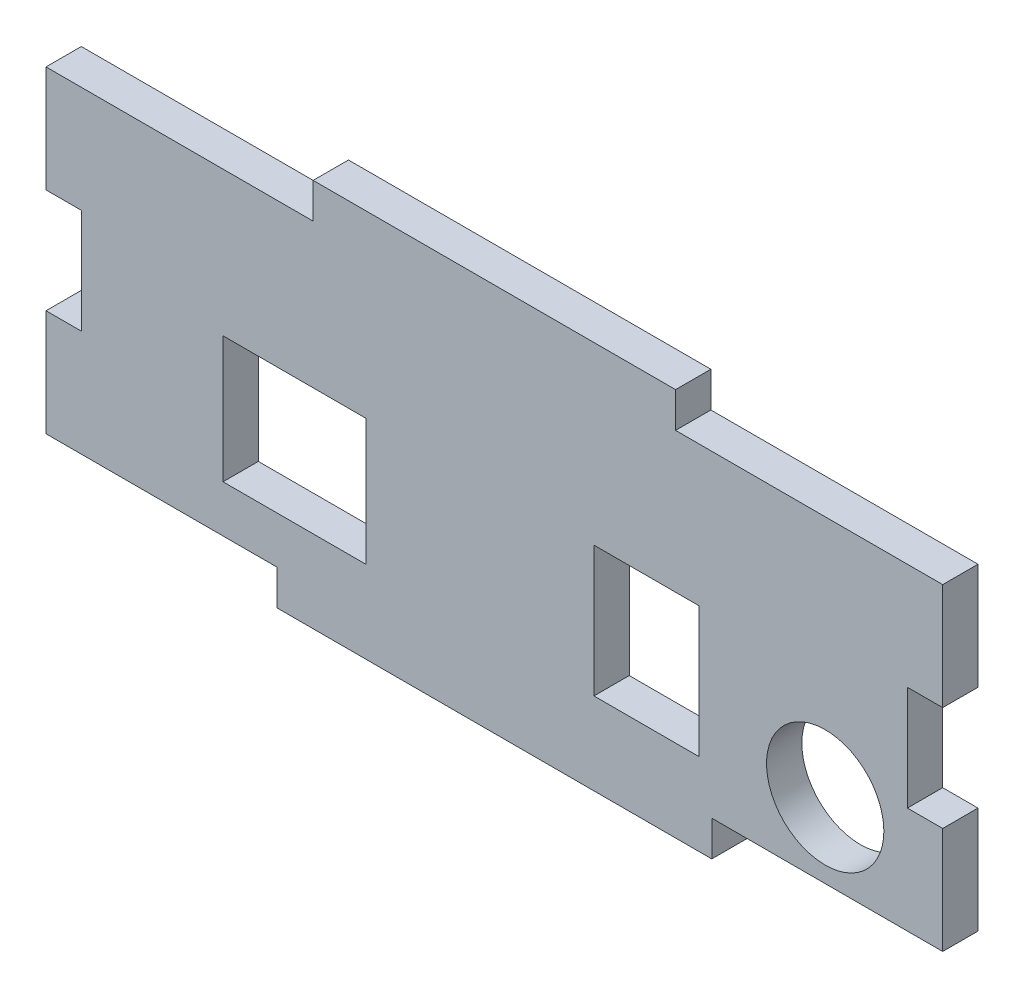
SolidWorks part; units mm, degrees
material "Acrylic (Medium-high impact)"
ref_plane "Front Plane" through (0, 0, 0) normal (0, 0, 1) x (1, 0, 0)
ref_plane "Top Plane" through (0, 0, 0) normal (0, 1, 0) x (1, 0, 0)
ref_plane "Right Plane" through (0, 0, 0) normal (1, 0, 0) x (0, 0, -1)
sketch "스케치1" plane through (0, 0, 0) normal (0, 0, 1) x (1, 0, 0)
  line L1 (-38.1, -15) -> (38.1, -15)
  line L2 (-38.1, -15) -> (-38.1, 15)
  line L3 (-38.1, 15) -> (38.1, 15)
  line L4 (38.1, -15) -> (38.1, 15)
  line L5 (-38.1, -15) -> (38.1, 15) construction
  line L6 (-38.1, 15) -> (38.1, -15) construction
  line L7 (-32.0618, -12) -> (21.075, -12) construction
  line L8 (-32.0618, -12) -> (-32.0618, -8.0122) construction
  line L9 (-32.0618, -8.0122) -> (21.075, -8.0122) construction
  line L10 (21.075, -12) -> (21.075, -8.0122) construction
  line L11 (-32.0618, -12) -> (21.075, -8.0122) construction
  line L12 (-32.0618, -8.0122) -> (21.075, -12) construction
  line L14 (8.4639, -8.0122) -> (17.4047, -8.0122)
  line L15 (8.4639, -8.0122) -> (8.4639, 3.0876)
  line L16 (8.4639, 3.0876) -> (17.4047, 3.0876)
  line L17 (17.4047, -8.0122) -> (17.4047, 3.0876)
  line L18 (8.4639, -8.0122) -> (17.4047, 3.0876) construction
  line L19 (8.4639, 3.0876) -> (17.4047, -8.0122) construction
  line L20 (-23.0575, -8.0122) -> (-10.9036, -8.0122)
  line L21 (-23.0575, -8.0122) -> (-23.0575, 2.732)
  line L22 (-23.0575, 2.732) -> (-10.9036, 2.732)
  line L23 (-10.9036, -8.0122) -> (-10.9036, 2.732)
  line L24 (-23.0575, -8.0122) -> (-10.9036, 2.732) construction
  line L25 (-23.0575, 2.732) -> (-10.9036, -8.0122) construction
  point P0 (0, 0)
  point P6 (-5.4934, -10.0061)
  point P17 (12.9343, -2.4623)
  point P22 (-16.9806, -2.6401)
  dimension "D1" = 76.2
  dimension "D2" = 53.1368
  dimension "D3" = 3.9878
  dimension "D4" = 3
  dimension "D5" = 8.9408
  dimension "D6" = 30
  dimension "D7" = 11.0998
  dimension "D8" = 10.7442
  dimension "D9" = 12.1539
  dimension "D10" = 19.3675
  dimension "D11" = 9.0043
  dimension "D12" = 17.025
extrude "보스-돌출1" add sketch "스케치1" along normal blind 3
sketch "스케치2" plane through (0, 0, 3) normal (0, 0, 1) x (1, 0, 0)
  line L0 (-38.1, -15) -> (38.1, -15) construction
  line L1 (-38.1, -15) -> (-18.4785, -15)
  line L2 (-38.1, -15) -> (-38.1, -12)
  line L3 (-38.1, -12) -> (-18.4785, -12)
  line L4 (-18.4785, -15) -> (-18.4785, -12)
  line L5 (-38.1, -15) -> (-18.4785, -12) construction
  line L6 (-38.1, -12) -> (-18.4785, -15) construction
  line L7 (18.4785, -15) -> (38.1, -15)
  line L8 (18.4785, -15) -> (18.4785, -12)
  line L9 (18.4785, -12) -> (38.1, -12)
  line L10 (38.1, -15) -> (38.1, -12)
  line L11 (18.4785, -15) -> (38.1, -12) construction
  line L12 (18.4785, -12) -> (38.1, -15) construction
  line L13 (38.1, -15) -> (38.1, 15) construction
  line L14 (18.4785, -12) -> (-18.4785, -12) construction
  point P4 (-28.2892, -13.5)
  point P10 (28.2892, -13.5)
  dimension "D1" = 36.957
  dimension "D2" = 3
extrude "컷-돌출1" cut sketch "스케치2" against normal up to surface (3 mm away) up to face at (0, 0, 0)
sketch "스케치3" plane through (0, 0, 3) normal (0, 0, 1) x (1, 0, 0)
  line L0 (-38.1, 15) -> (-38.1, -12) construction
  line L1 (-38.1, -2.945) -> (-35.1, -2.945)
  line L2 (-38.1, -2.945) -> (-38.1, 5.945)
  line L3 (-38.1, 5.945) -> (-35.1, 5.945)
  line L4 (-35.1, -2.945) -> (-35.1, 5.945)
  line L5 (-38.1, -2.945) -> (-35.1, 5.945) construction
  line L6 (-38.1, 5.945) -> (-35.1, -2.945) construction
  line L7 (38.1, -12) -> (38.1, 15) construction
  line L8 (38.1, 5.945) -> (35.1, 5.945)
  line L9 (38.1, 5.945) -> (38.1, -2.945)
  line L10 (38.1, -2.945) -> (35.1, -2.945)
  line L11 (35.1, 5.945) -> (35.1, -2.945)
  line L12 (38.1, 5.945) -> (35.1, -2.945) construction
  line L13 (38.1, -2.945) -> (35.1, 5.945) construction
  line L14 (38.1, 1.5) -> (-38.1, 1.5) construction
  point P4 (-36.6, 1.5)
  point P11 (36.6, 1.5)
  dimension "D1" = 8.89
  dimension "D2" = 3
extrude "컷-돌출2" cut sketch "스케치3" against normal up to surface (3 mm away) up to face at (0, -6, 0)
sketch "스케치4" plane through (0, 0, 3) normal (0, 0, 1) x (1, 0, 0)
  line L0 (38.1, 15) -> (-38.1, 15) construction
  line L1 (-15.3987, 18) -> (15.3988, 18)
  line L2 (-15.3987, 18) -> (-15.3987, 15)
  line L3 (-15.3987, 15) -> (15.3988, 15)
  line L4 (15.3988, 18) -> (15.3988, 15)
  line L5 (-15.3987, 18) -> (15.3988, 15) construction
  line L6 (-15.3987, 15) -> (15.3988, 18) construction
  line L7 (0, 16.5) -> (0, 0) construction
  point P0 (0, 16.5)
  dimension "D1" = 30.7975
  dimension "D2" = 3
extrude "보스-돌출2" add sketch "스케치4" against normal up to surface (3 mm away) up to face at (0, -2.25, 0)
sketch "스케치5" plane through (0, 0, 3) normal (0, 0, 1) x (1, 0, 0)
  line L0 (38.1, -12) -> (18.4785, -12) construction
  line L1 (35.1, 5.945) -> (35.1, -2.945) construction
  line L2 (21.13, 0.7) -> (35.1, 0.7) construction
  line L3 (21.13, 0.7) -> (21.13, -12) construction
  line L4 (21.13, -12) -> (35.1, -12) construction
  line L5 (35.1, 0.7) -> (35.1, -12) construction
  line L6 (21.13, 0.7) -> (35.1, -12) construction
  line L7 (21.13, -12) -> (35.1, 0.7) construction
  circle A0 centre (28.115, -5.65) radius 4.9847
  dimension "D1" = 9.9695
  dimension "D2" = 13.97
  dimension "D3" = 12.7
extrude "컷-돌출3" cut sketch "스케치5" against normal up to surface (3 mm away) up to face at (0, 1.5, 0)
